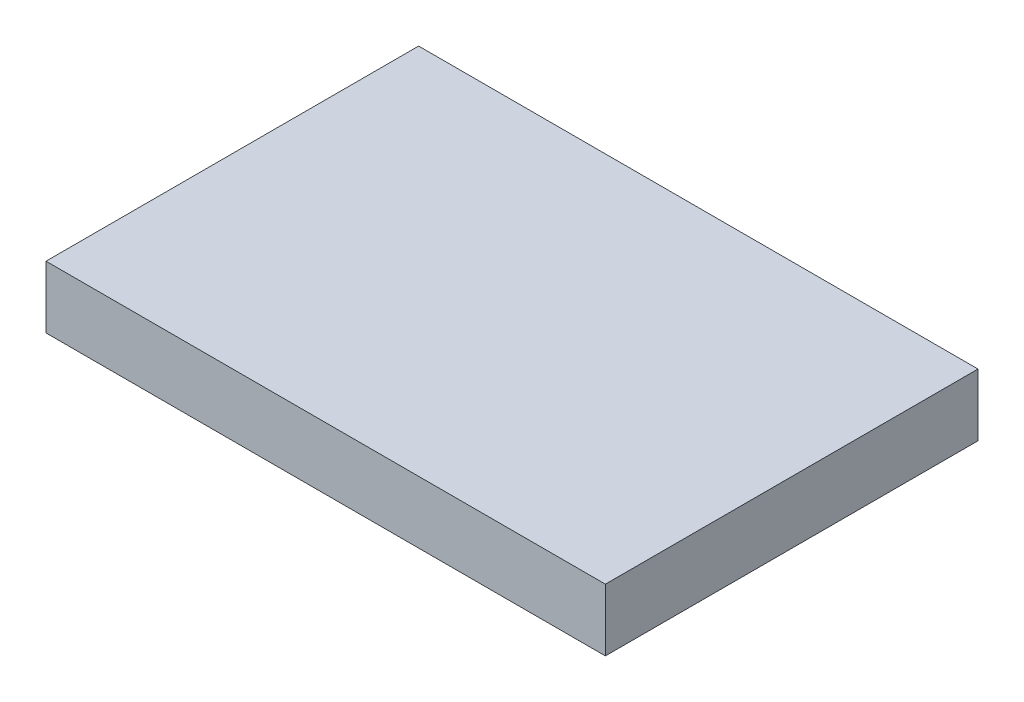
SolidWorks part; units mm, degrees
ref_plane "Front Plane" through (0, 0, 0) normal (0, 0, 1) x (1, 0, 0)
ref_plane "Top Plane" through (0, 0, 0) normal (0, 1, 0) x (1, 0, 0)
ref_plane "Right Plane" through (0, 0, 0) normal (1, 0, 0) x (0, 0, -1)
sketch "Sketch1" plane through (0, 0, 0) normal (0, 1, 0) x (1, 0, 0)
  line L1 (0, 0) -> (-114.261, 0)
  line L2 (0, 0) -> (0, 76.1093)
  line L3 (0, 76.1093) -> (-114.261, 76.1093)
  line L4 (-114.261, 0) -> (-114.261, 76.1093)
extrude "Boss-Extrude1" add sketch "Sketch1" against normal blind 12.7 contours L2 L1 L4 L3
